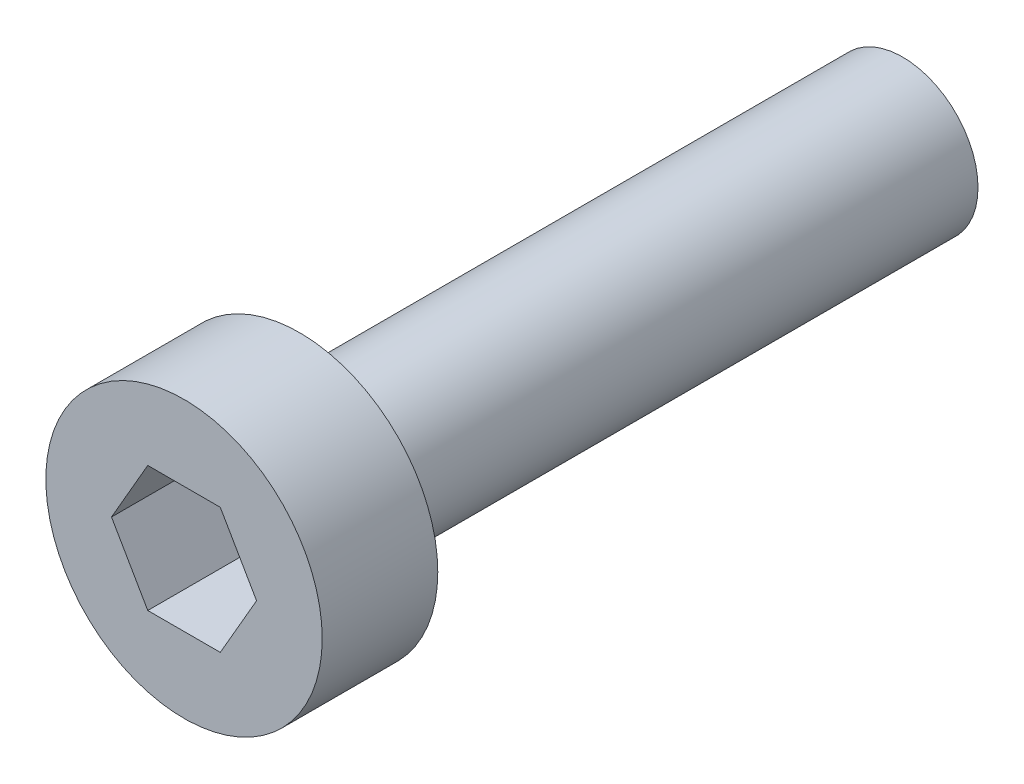
SolidWorks part; units mm, degrees
ref_plane "Plan de face" through (0, 0, 0) normal (0, 0, 1) x (1, 0, 0)
ref_plane "Plan de dessus" through (0, 0, 0) normal (0, 1, 0) x (1, 0, 0)
ref_plane "Plan de droite" through (0, 0, 0) normal (1, 0, 0) x (0, 0, -1)
sketch "Esquisse1" plane through (0, 0, 0) normal (0, 0, 1) x (1, 0, 0)
  circle A0 centre (0, 0) radius 1.5
  dimension "D1" = 3
extrude "Boss.-Extru.1" add sketch "Esquisse1" along normal blind 12
sketch "Esquisse2" plane through (0, 0, 12) normal (0, 0, 1) x (1, 0, 0)
  circle A0 centre (0, 0) radius 2.75
  dimension "D1" = 5.5
extrude "Boss.-Extru.2" add sketch "Esquisse2" along normal blind 2.3
sketch "Esquisse3" plane through (0, 0, 14.3) normal (0, 0, 1) x (1, 0, 0)
  line L1 (1.4434, 0) -> (0.7217, 1.25)
  line L2 (0.7217, 1.25) -> (-0.7217, 1.25)
  line L3 (-0.7217, 1.25) -> (-1.4434, 0)
  line L4 (-1.4434, 0) -> (-0.7217, -1.25)
  line L5 (-0.7217, -1.25) -> (0.7217, -1.25)
  line L6 (0.7217, -1.25) -> (1.4434, 0)
  circle A0 centre (0, 0) radius 1.25 construction
  dimension "D1" = 2.5
extrude "Enlèv. mat.-Extru.1" cut sketch "Esquisse3" against normal blind 2
